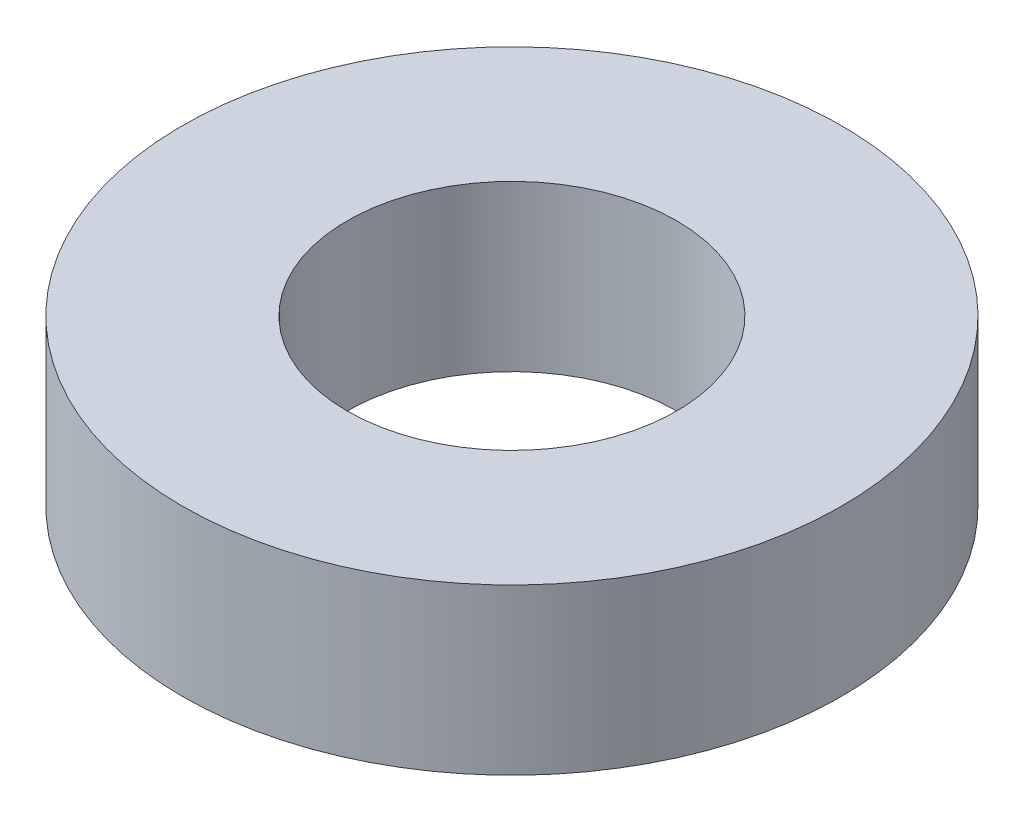
SolidWorks part; units mm, degrees
ref_plane "Front Plane" through (0, 0, 0) normal (0, 0, 1) x (1, 0, 0)
ref_plane "Top Plane" through (0, 0, 0) normal (0, 1, 0) x (1, 0, 0)
ref_plane "Right Plane" through (0, 0, 0) normal (1, 0, 0) x (0, 0, -1)
sketch "Sketch1" plane through (0, 0, 0) normal (0, 1, 0) x (1, 0, 0)
  circle A0 centre (0, 0) radius 4
  circle A1 centre (0, 0) radius 2
  dimension "D1" = 4
  dimension "D2" = 8
extrude "Boss-Extrude1" add sketch "Sketch1" along normal mid plane 2
